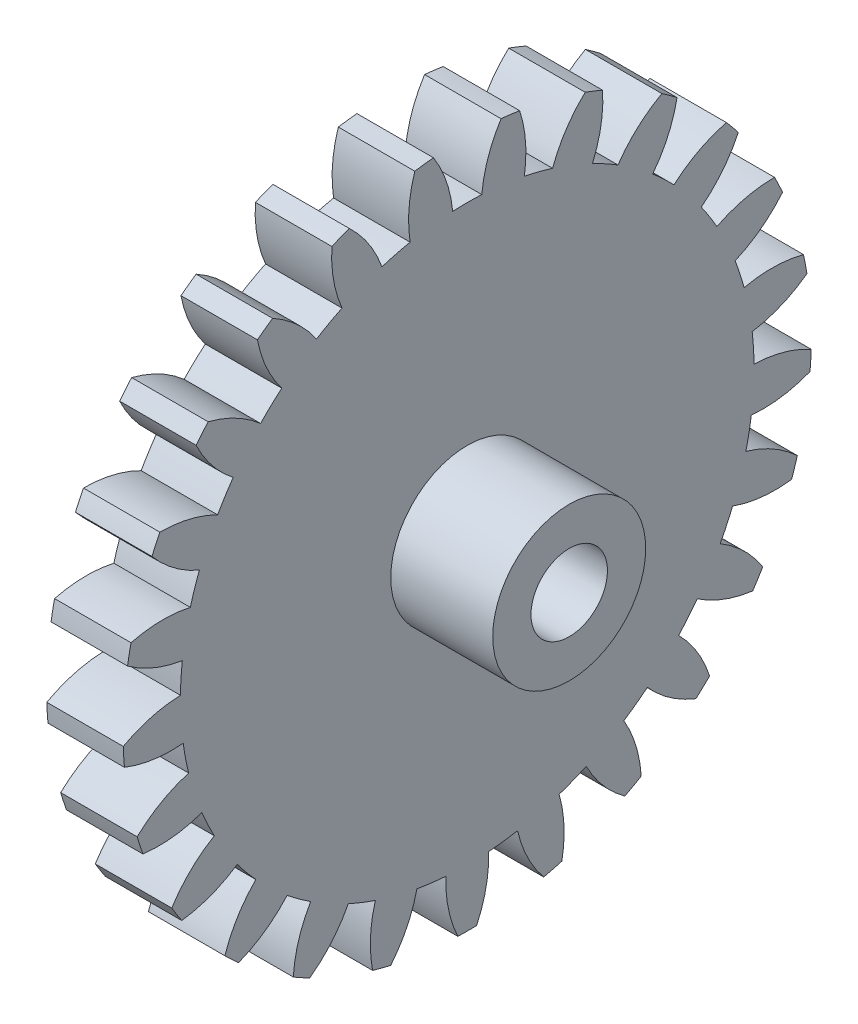
SolidWorks part; units mm, degrees
ref_plane "Plane1" through (0, 0, 0) normal (0, 0, 1) x (1, 0, 0)
ref_plane "Plane2" through (0, 0, 0) normal (0, 1, 0) x (1, 0, 0)
ref_plane "Plane3" through (0, 0, 0) normal (1, 0, 0) x (0, 0, -1)
sketch "HoldingSke" plane through (0, 0, 0) normal (0, 1, 0) x (1, 0, 0)
  line L0 (0, 0) -> (0.9063, -0.4226)
  line L1 (-15, 0) -> (100, 0) construction
  line L2 (0, 0) -> (-2.1039, 2.3779)
  line L3 (0, 0) -> (-11.863, 4.5341)
  line L4 (0, 0) -> (7.8269, 3.6497)
  line L5 (0, 0) -> (-4.6848, -1.7473)
  line L6 (0, 0) -> (-2.4869, -1.6779)
  line L7 (-2.1039, 2.3779) -> (-1.0276, 7.2607)
  line L8 (-76.2, 54.61) -> (-75.7, 54.61)
  line L9 (-67.7845, 28.3722) -> (-49.3413, 33.142)
  line L10 (-76.2, 71.12) -> (104.1128, 71.12)
  line L11 (0, 0) -> (-3, 0)
  line L12 (-76.2, 101.6) -> (-76.162, 101.6)
  line L13 (24.9733, 27.94) -> (52.9518, 28.4284)
  line L14 (24.9733, 27.94) -> (24.9743, 27.94)
  line L15 (24.9733, 27.94) -> (100.4006, 29.5858)
  line L16 (-63.627, -1) -> (-12.827, -1)
  circle A0 centre (0, 0) radius 1.5
  circle A1 centre (0, 0) radius 3
  circle A2 centre (0, 0) radius 3
  circle A3 centre (0, 0) radius 1.5
  dimension "MHD" = 6
  dimension "Hub_dia" = 6
  dimension "Bore" = 3
  dimension "MBD" = 3
  dimension "Num_teeth" = 25
  dimension "Pitch" = 1
  dimension "Overall_len" = 5
  dimension "Show_teeth" = 25
  dimension "Thickness" = 3
  dimension "OAL" = 5.0001
  dimension "T_dim" = 0.5
  dimension "Ap" = 14.5
  dimension "H" = 19.05
  dimension "Pitch_radius" = 180.3128
  dimension "Width" = 3
  dimension "Backlash" = 0.038
  dimension "Addendum_fac" = 1
  dimension "Dedendum_fac" = 1.25
  dimension "Clearance_fac" = 0.25
  dimension "Dedendum_add" = 0.001
  dimension "Module" = 1
sketch "BasProSke" plane through (0, 0, 0) normal (0, 1, 0) x (1, 0, 0)
  line L0 (-10, 0) -> (60, 0) construction
  line L1 (0, 0) -> (0, 13.5)
  line L2 (0, 0) -> (3, 0)
  line L3 (3, 0) -> (3, 13.5)
  line L4 (3, 13.5) -> (0, 13.5)
  dimension "Thickness" = 3
  dimension "Diameter" = 27
revolve "Base-Revolve" add sketch "BasProSke" angle 360 about L0
sketch "TooCutSke" plane through (0, 0, 0) normal (1, 0, 0) x (0, 0, -1)
  line L1 (0, 0) -> (0, 107) construction
  line L2 (0, 0) -> (-0.8514, 12.471) construction
  line L3 (0, 0) -> (-3.1282, 24.7619) construction
  line L4 (-0.8514, 12.471) -> (-1.5641, 12.3809) construction
  arc A0 (0.5708, 11.2345) -> (-0.5708, 11.2345) centre (0, 0) ccw
  arc A1 (1.3416, 13.4587) -> (-1.3416, 13.4587) centre (0, 0) ccw
  circle A2 centre (0, 0) radius 12.5 construction
  circle A3 centre (0, 0) radius 12.1018 construction
  arc A4 (-0.5708, 11.2345) -> (-1.3416, 13.4587) centre (-5.5478, 10.7553) ccw
  arc A5 (1.3416, 13.4587) -> (0.5708, 11.2345) centre (5.5478, 10.7553) ccw
  dimension "Root_dia" = 22.498
  dimension "Overcut_dia" = 27.0508
  dimension "Pitch_dia" = 25
  dimension "Base_dia" = 24.2037
  dimension "Flank_rad" = 5
  dimension "Half_ang" = 7.2
  dimension "Half_CT" = 0.7184
extrude "ToothCut" cut sketch "TooCutSke" along normal through all
fillet "Breaks" [suppressed] radius 0.02
fillet "RootFillets" [suppressed] radius 0.251
pattern_circular "TeethCuts" count 25 over 360 about axis through (0, 0, 0) along (1, 0, 0) of "ToothCut", "RootFillets", "Breaks"
sketch "HubNeaOneSke" plane through (0, 0, 0) normal (-1, 0, 0) x (0, 0, 1)
  circle A0 centre (0, 0) radius 3
  dimension "Diameter" = 6
extrude "HubNearOne" [suppressed] add sketch "HubNeaOneSke" along normal blind 2.0001
sketch "HubNeaBotSke" plane through (0, 0, 0) normal (-1, 0, 0) x (0, 0, 1)
  circle A0 centre (0, 0) radius 3
  dimension "Diameter" = 6
extrude "HubNearBoth" add sketch "HubNeaBotSke" along normal blind 1
ref_plane "FarPln" through (3, 0, 0) normal (1, 0, 0) x (0, 0, -1)
sketch "HubFarSke" plane through (3, 0, 0) normal (1, 0, 0) x (0, 0, -1)
  circle A0 centre (0, 0) radius 3
  dimension "Diameter" = 6
extrude "HubFar" add sketch "HubFarSke" along normal blind 1
sketch "BorSke" plane through (0, 0, 0) normal (1, 0, 0) x (0, 0, -1)
  circle A0 centre (0, 0) radius 1.5
  dimension "Diameter" = 3
extrude "Bore" cut sketch "BorSke" along normal mid plane 10.0001
sketch "KeySke" plane through (0, 0, 0) normal (1, 0, 0) x (0, 0, -1)
  line L0 (-0.6, 0) -> (-0.6, 2)
  line L1 (-0.6, 2) -> (0.6, 2)
  line L2 (0.6, 2) -> (0.6, 0)
  line L3 (0, 0) -> (0, 34) construction
  line L4 (-0.6, 0) -> (0.6, 0)
  dimension "Offset" = 2
  dimension "Width" = 1.2
extrude "Keyway" [suppressed] cut sketch "KeySke" along normal mid plane 10.0001
pattern_circular "Keyway2" [suppressed] count 2 every 90 about axis through (-10, 0, 0) along (1, 0, 0)
sketch "Sketch1" plane through (4, 0, 0) normal (1, 0, 0) x (0, 0, -1)
  circle A1 centre (0, 0) radius 3
  circle A2 centre (0, 0) radius 3
  circle M2 centre (0, 0) radius 1.5
  circle M3 centre (0, 0) radius 3
  dimension "D1" = 0
extrude "Boss-Extrude1" add sketch "Sketch1" along normal blind 3 contours M3 M2
equation "' \"Module@HoldingSke\" = 6.35"
equation "' \"Num_teeth@HoldingSke\" = 12"
equation "' \"Ap@HoldingSke\" =  20"
equation "' \"Ap@HoldingSke\" = 20"
equation "' \"Width@HoldingSke\" = 0.5 * 25.4"
equation "' \"Hub_dia@HoldingSke\"= 1 * 25.4"
equation "' \"Hub_dia@HoldingSke\" = 1 * 25.4"
equation "' \"Overall_len@HoldingSke\" = 1.0 * 25.4"
equation "' \"Bore@HoldingSke\" = 0.75 * 25.4"
equation "' \"T_dim@HoldingSke\" = 0.1 * 25.4"
equation "' \"Width@KeySke\" = 0.25 * 25.4"
equation "' \"Show_teeth@HoldingSke\" = 13"
equation "' \"Backlash@HoldingSke\" = 0.009 * 25.4"
equation "' \"Addendum_fac@HoldingSke\" = 1.0"
equation "' \"Dedendum_fac@HoldingSke\" = 1.25"
equation "' \"Dedendum_add@HoldingSke\" = 0.00005 * 25.4"
equation "' \"Clearance_fac@HoldingSke\" = 0.25"
equation "\"Pitch@HoldingSke\" = 1 / \"Module@HoldingSke\""
equation "\"Overcut_dia@TooCutSke\" = (\"Num_teeth@HoldingSke\" + 2 * \"Addendum_fac@HoldingSke\") / \"Pitch@HoldingSke\" + 0.002 * 25.4"
equation "\"Pitch_dia@TooCutSke\" = \"Num_teeth@HoldingSke\" / \"Pitch@HoldingSke\""
equation "\"Base_dia@TooCutSke\" = \"Num_teeth@HoldingSke\" / \"Pitch@HoldingSke\" * cos((\"Ap@HoldingSke\"  * 3.14159265 / 180))"
equation "\"Root_dia@TooCutSke\" = (\"Num_teeth@HoldingSke\" + 2) / \"Pitch@HoldingSke\" - 2 * (\"Addendum_fac@HoldingSke\" + \"Dedendum_fac@HoldingSke\") / \"Pitch@HoldingSke\" - \"Dedendum_add@HoldingSke\" * 2"
equation "\"Half_ang@TooCutSke\" = 180 / \"Num_teeth@HoldingSke\""
equation "\"Half_CT@TooCutSke\" = \"Num_teeth@HoldingSke\" / \"Pitch@HoldingSke\" * sin((3.14159265 / 2 / \"Num_teeth@HoldingSke\")) / 2 - 7 * \"Backlash@HoldingSke\" / 4"
equation "\"Flank_rad@TooCutSke\" = \"Num_teeth@HoldingSke\" / \"Pitch@HoldingSke\" / 5"
equation "\"Radius@RootFillets\" = \"Clearance_fac@HoldingSke\" / \"Pitch@HoldingSke\" + \"Dedendum_add@HoldingSke\""
equation "\"Break_rad@Breaks\" = 0.02 / \"Pitch@HoldingSke\""
equation "\"Thickness@HoldingSke\" = \"Width@HoldingSke\""
equation "\"OAL@HoldingSke\" = \"Thickness@HoldingSke\""
equation "\"MHD@HoldingSke\" = (\"Num_teeth@HoldingSke\" + 2) / \"Pitch@HoldingSke\" - 2 * (\"Addendum_fac@HoldingSke\" + \"Dedendum_fac@HoldingSke\")  / \"Pitch@HoldingSke\" - \"Dedendum_add@HoldingSke\" * 2"
equation "\"MBD@HoldingSke\" = (\"Num_teeth@HoldingSke\" + 2) / \"Pitch@HoldingSke\" - 2 * (\"Addendum_fac@HoldingSke\" + \"Dedendum_fac@HoldingSke\")  / \"Pitch@HoldingSke\" - \"Dedendum_add@HoldingSke\" * 2 - 0.002 * 25.4"
equation "\"MHD@HoldingSke\" = ((sgn( \"MHD@HoldingSke\" - \"Hub_dia@HoldingSke\" )-1)*( \"MHD@HoldingSke\" - \"Hub_dia@HoldingSke\" ))/-2+ \"Hub_dia@HoldingSke\""
equation "\"MBD@HoldingSke\" = ((sgn( \"MBD@HoldingSke\" - \"Bore@HoldingSke\" )-1)*( \"MBD@HoldingSke\" - \"Bore@HoldingSke\" ))/-2+ \"Bore@HoldingSke\""
equation "\"OAL@HoldingSke\" = ((sgn( \"OAL@HoldingSke\" - \"Overall_len@HoldingSke\" )+1)*( \"OAL@HoldingSke\" - \"Overall_len@HoldingSke\" ))/2 + \"Overall_len@HoldingSke\" + 0.000002 * 25.4"
equation "\"Num_teeth@TeethCuts\" = int( \"Show_teeth@HoldingSke\" ) + 1"
equation "\"Num_teeth@TeethCuts\" = ((sgn( \"Num_teeth@TeethCuts\" - \"Num_teeth@HoldingSke\" )-1)*( \"Num_teeth@TeethCuts\" - \"Num_teeth@HoldingSke\" ))/-2+ \"Num_teeth@HoldingSke\""
equation "\"Num_teeth@TeethCuts\" = ((sgn( \"Num_teeth@TeethCuts\" - 2.0)+1)*( \"Num_teeth@TeethCuts\" - 2.0))/2 +2.0"
equation "\"Angle@TeethCuts\" = 360.0 / \"Num_teeth@HoldingSke\""
equation "\"Diameter@BasProSke\" = (\"Num_teeth@HoldingSke\" + 2 * \"Addendum_fac@HoldingSke\") / \"Pitch@HoldingSke\""
equation "\"Thickness@BasProSke\"  = \"Thickness@HoldingSke\""
equation "' \"Fillet_rad@BasProSke\" =  \"Thickness@HoldingSke\" * 0.05"
equation "' \"Fillet_rad@BasProSke\" = \"Thickness@HoldingSke\" * 0.05"
equation "\"MHD@HoldingSke\" = ((sgn( \"MHD@HoldingSke\" - \"Root_dia@TooCutSke\" )-1)*( \"MHD@HoldingSke\" - \"Root_dia@TooCutSke\" ))/-2+ \"Root_dia@TooCutSke\""
equation "\"Diameter@HubNeaOneSke\" = \"MHD@HoldingSke\""
equation "\"Length@HubNearOne\" = \"OAL@HoldingSke\" - \"Thickness@BasProSke\""
equation "\"Diameter@HubNeaBotSke\" = \"MHD@HoldingSke\""
equation "\"Length@HubNearBoth\" = ( \"OAL@HoldingSke\" - \"Thickness@BasProSke\" ) / 2.0"
equation "\"Thickness@FarPln\" = \"Thickness@BasProSke\""
equation "\"Diameter@HubFarSke\" = \"MHD@HoldingSke\""
equation "\"Length@HubFar\" = ( \"OAL@HoldingSke\" - \"Thickness@BasProSke\" ) / 2.0"
equation "\"Diameter@BorSke\" = \"MBD@HoldingSke\""
equation "\"D1@Bore\" = \"OAL@HoldingSke\" * 2.0"
equation "\"D1@Keyway\" = \"OAL@HoldingSke\" * 2.0"
equation "\"Offset@KeySke\" = \"T_dim@HoldingSke\" + \"MBD@HoldingSke\" / 2.0"
